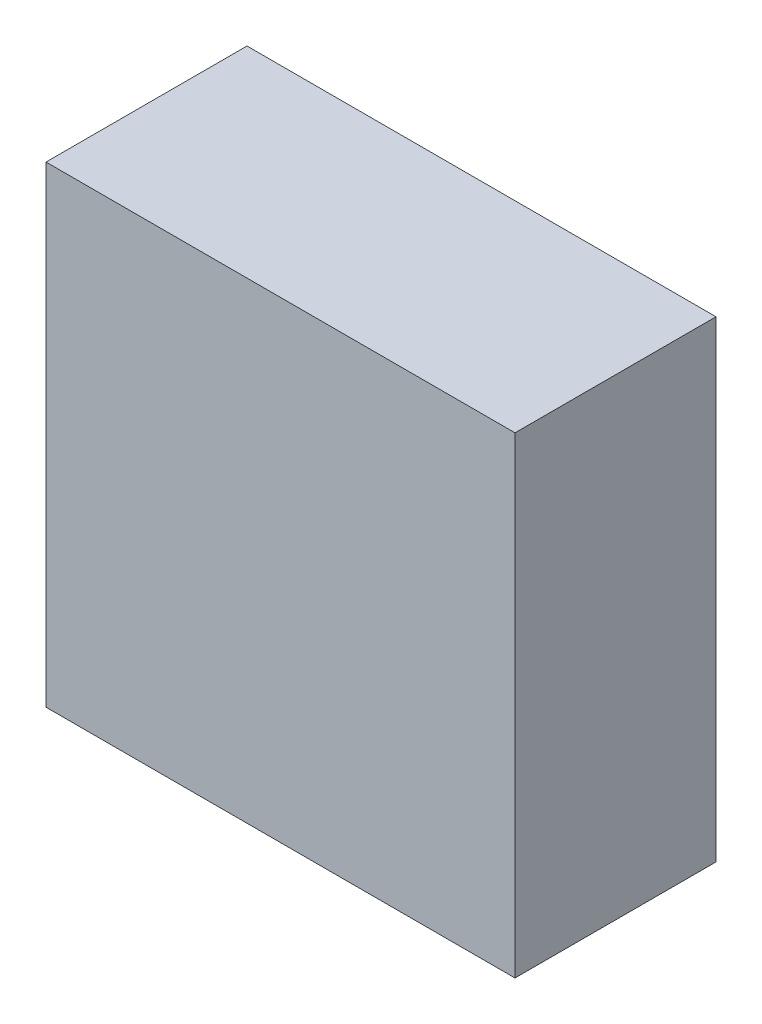
SolidWorks part; units mm, degrees
material "Pine"
ref_plane "Front Plane" through (0, 0, 0) normal (0, 0, 1) x (1, 0, 0)
ref_plane "Top Plane" through (0, 0, 0) normal (0, 1, 0) x (1, 0, 0)
ref_plane "Right Plane" through (0, 0, 0) normal (1, 0, 0) x (0, 0, -1)
sketch "Sketch1" plane through (0, 0, 0) normal (0, 1, 0) x (1, 0, 0)
  line L1 (-44.45, 19.05) -> (44.45, 19.05)
  line L2 (-44.45, 19.05) -> (-44.45, -19.05)
  line L4 (44.45, 19.05) -> (44.45, -19.05)
  line L5 (-44.45, 19.05) -> (44.45, -19.05) construction
  line L6 (-44.45, -19.05) -> (44.45, 19.05) construction
  line L7 (-44.45, -19.05) -> (44.45, -19.05)
  point P0 (0, 0)
  dimension "D1" = 88.9
  dimension "D2" = 38.1
extrude "Boss-Extrude1" add sketch "Sketch1" along normal blind 89.5 contours L2 L4 L1
sketch "Sketch2" plane through (-44.45, 0, 0) normal (-1, 0, 0) x (0, 0, 1)
  line L0 (-19.05, 0) -> (19.05, 6.7181)
  line L1 (19.05, 89.5) -> (19.05, 0) construction
  line L2 (19.05, 6.7181) -> (19.05, 0)
  line L3 (19.05, 0) -> (-19.05, 0)
  dimension "D1" = 10
